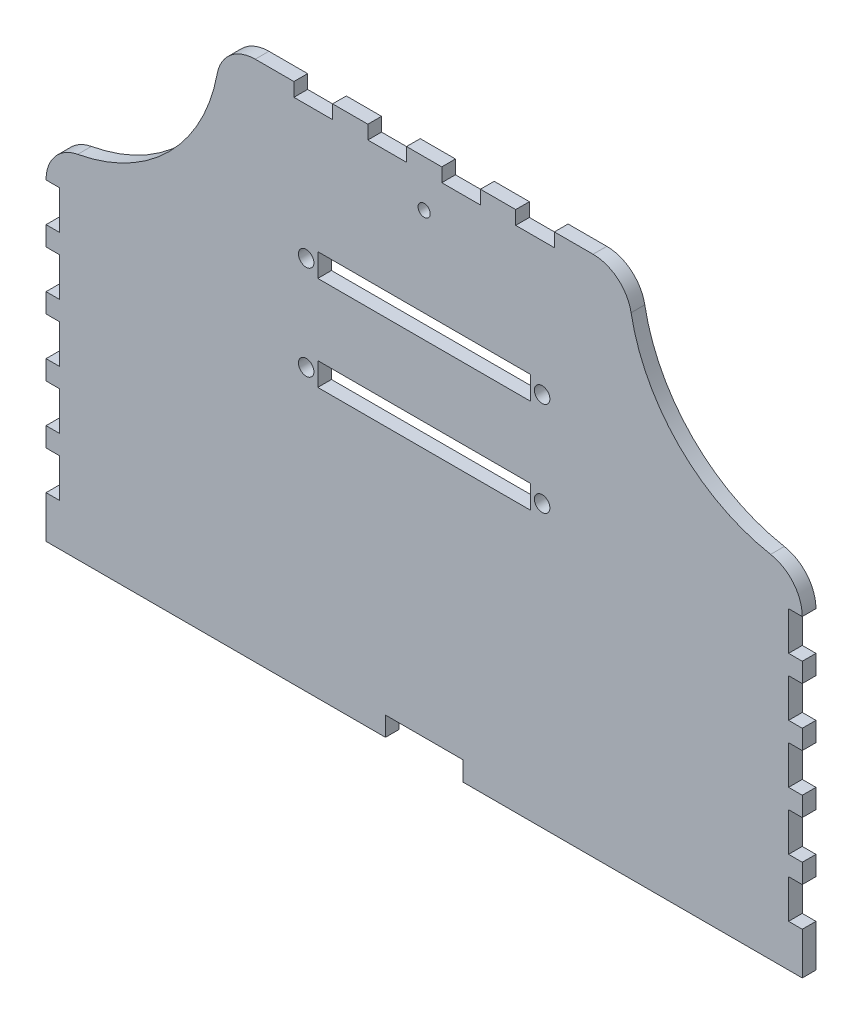
SolidWorks part; units mm, degrees
ref_plane "Front Plane" through (0, 0, 0) normal (0, 0, 1) x (1, 0, 0)
ref_plane "Top Plane" through (0, 0, 0) normal (0, 1, 0) x (1, 0, 0)
ref_plane "Right Plane" through (0, 0, 0) normal (1, 0, 0) x (0, 0, -1)
sketch "Sketch1" plane through (0, 0, 0) normal (0, 0, 1) x (1, 0, 0)
  line L1 (0, 0) -> (248.285, 0)
  line L2 (0, 0) -> (0, 171.45)
  line L3 (0, 171.45) -> (248.285, 171.45)
  line L4 (248.285, 0) -> (248.285, 171.45)
  circle A0 centre (0, 171.45) radius 57.15
  circle A1 centre (248.285, 171.45) radius 57.15
  dimension "D3" = 114.3
  dimension "D1" = 171.45
  dimension "D2" = 248.285
extrude "Boss-Extrude1" add sketch "Sketch1" along normal blind 4.4958 contours A1 L3 A0 L2 L1 L4
fillet "Fillet1" radius 12.7 4 edges at (0, 114.3, 2.2479) (248.285, 114.3, 2.2479) (191.135, 171.45, 2.2479) (57.15, 171.45, 2.2479)
sketch "Sketch2" plane through (0, 0, 4.4958) normal (0, 0, 1) x (1, 0, 0)
  line L0 (0, 83.7142) -> (4.4958, 83.7142)
  line L1 (0, 102.7642) -> (4.4958, 102.7642)
  line L2 (0, 102.7642) -> (0, 90.0642)
  line L3 (0, 90.0642) -> (4.4958, 90.0642)
  line L4 (4.4958, 102.7642) -> (4.4958, 90.0642)
  line L5 (4.4958, 83.7142) -> (4.4958, 71.0142)
  line L6 (0, 71.0142) -> (4.4958, 71.0142)
  line L7 (0, 64.6642) -> (4.4958, 64.6642)
  line L8 (4.4958, 64.6642) -> (4.4958, 51.9642)
  line L9 (0, 51.9642) -> (4.4958, 51.9642)
  line L10 (0, 45.6142) -> (4.4958, 45.6142)
  line L11 (4.4958, 45.6142) -> (4.4958, 32.9142)
  line L12 (0, 32.9142) -> (4.4958, 32.9142)
  line L13 (0, 26.5642) -> (4.4958, 26.5642)
  line L14 (4.4958, 26.5642) -> (4.4958, 13.8642)
  line L15 (0, 13.8642) -> (4.4958, 13.8642)
  line L16 (124.1425, 171.45) -> (124.1425, 0) construction
  line L17 (68.6858, 171.45) -> (179.5992, 171.45) construction
  line L18 (0, 0) -> (248.285, 0) construction
  line L19 (248.285, 13.8642) -> (243.7892, 13.8642)
  line L20 (243.7892, 26.5642) -> (243.7892, 13.8642)
  line L21 (248.285, 26.5642) -> (243.7892, 26.5642)
  line L22 (248.285, 32.9142) -> (243.7892, 32.9142)
  line L23 (243.7892, 45.6142) -> (243.7892, 32.9142)
  line L24 (248.285, 45.6142) -> (243.7892, 45.6142)
  line L25 (248.285, 51.9642) -> (243.7892, 51.9642)
  line L26 (243.7892, 64.6642) -> (243.7892, 51.9642)
  line L27 (248.285, 64.6642) -> (243.7892, 64.6642)
  line L28 (243.7892, 83.7142) -> (243.7892, 71.0142)
  line L29 (248.285, 83.7142) -> (243.7892, 83.7142)
  line L30 (248.285, 71.0142) -> (243.7892, 71.0142)
  line L31 (248.285, 90.0642) -> (243.7892, 90.0642)
  line L32 (243.7892, 102.7642) -> (243.7892, 90.0642)
  line L33 (248.285, 102.7642) -> (243.7892, 102.7642)
  line L34 (248.285, 102.7642) -> (248.285, 90.0642)
  line M20 (0, 102.7642) -> (0, 0)
  line M22 (248.285, 0) -> (248.285, 102.7642)
  dimension "D2" = 4.4958
  dimension "D3" = 12.7
  dimension "D1" = 5
extrude "Cut-Extrude1" cut sketch "Sketch2" against normal through all contours L33 L32 L31 M22 | L30 L29 L28 M22 | L24 L23 L22 M22 | L27 L26 L25 M22 | L21 L20 L19 M22 | L4 L1 L3 M20 | L6 L5 L0 M20 | L9 L8 L7 M20 | L12 L11 L10 M20 | L15 L14 L13 M20
sketch "Sketch3" plane through (0, 0, 4.4958) normal (0, 0, 1) x (1, 0, 0)
  line L0 (105.6569, 171.45) -> (105.6569, 166.9542)
  line L1 (81.3858, 171.45) -> (94.0858, 171.45)
  line L2 (81.3858, 171.45) -> (81.3858, 166.9542)
  line L3 (81.3858, 166.9542) -> (94.0858, 166.9542)
  line L4 (94.0858, 171.45) -> (94.0858, 166.9542)
  line L5 (105.6569, 171.45) -> (118.3569, 171.45)
  line L6 (118.3569, 171.45) -> (118.3569, 166.9542)
  line L7 (105.6569, 166.9542) -> (118.3569, 166.9542)
  line L8 (129.9281, 171.45) -> (129.9281, 166.9542)
  line L9 (129.9281, 171.45) -> (142.6281, 171.45)
  line L10 (142.6281, 171.45) -> (142.6281, 166.9542)
  line L11 (129.9281, 166.9542) -> (142.6281, 166.9542)
  line L12 (154.1992, 171.45) -> (154.1992, 166.9542)
  line L13 (154.1992, 171.45) -> (166.8992, 171.45)
  line L14 (166.8992, 171.45) -> (166.8992, 166.9542)
  line L15 (154.1992, 166.9542) -> (166.8992, 166.9542)
  line L16 (68.6858, 171.45) -> (179.5992, 171.45) construction
  dimension "D1" = 12.7
  dimension "D2" = 12.7
  dimension "D3" = 4.4958
  dimension "D5" = 12.7
  dimension "D4" = 4
extrude "Cut-Extrude2" cut sketch "Sketch3" against normal through all
sketch "Sketch4" [suppressed] plane through (0, 0, 4.4958) normal (0, 0, 1) x (1, 0, 0)
  line L0 (0, 0) -> (248.285, 0) construction
  line L1 (248.285, 0) -> (248.285, 13.8642) construction
  circle A0 centre (210.185, 19.05) radius 5.08
  dimension "D1" = 10.16
  dimension "D2" = 19.05
  dimension "D3" = 38.1
extrude "Cut-Extrude3" [suppressed] cut sketch "Sketch4" against normal through all
sketch "Sketch5" plane through (0, 0, 4.4958) normal (0, 0, 1) x (1, 0, 0)
  line L0 (0, 0) -> (248.285, 0) construction
  line L1 (111.4425, 0) -> (136.8425, 0)
  line L2 (111.4425, 0) -> (111.4425, 6.35)
  line L3 (111.4425, 6.35) -> (136.8425, 6.35)
  line L4 (136.8425, 0) -> (136.8425, 6.35)
  point P6 (124.1425, 0)
  point P7 (124.1425, 0)
  dimension "D1" = 25.4
  dimension "D2" = 6.35
extrude "Cut-Extrude4" cut sketch "Sketch5" against normal through all
sketch "Sketch6" [suppressed] plane through (0, 0, 0) normal (0, 0, -1) x (-1, 0, 0)
  line L0 (-136.8425, 6.35) -> (-111.4425, 6.35) construction
  line L1 (-149.5425, 76.2) -> (-98.7425, 76.2)
  line L2 (-149.5425, 76.2) -> (-149.5425, 50.8)
  line L3 (-149.5425, 50.8) -> (-98.7425, 50.8)
  line L4 (-98.7425, 76.2) -> (-98.7425, 50.8)
  line L5 (0, 0) -> (-111.4425, 0) construction
  point P4 (-124.1425, 50.8)
  point P7 (-124.1425, 6.35)
  dimension "D1" = 50.8
  dimension "D2" = 25.4
  dimension "D3" = 50.8
extrude "Cut-Extrude5" [suppressed] cut sketch "Sketch6" against normal through all
sketch "Sketch7" plane through (0, 0, 0) normal (0, 0, -1) x (-1, 0, 0)
  line L0 (-136.8425, 6.35) -> (-111.4425, 6.35) construction
  line L1 (-159.0675, 127) -> (-89.2175, 127)
  line L2 (-159.0675, 127) -> (-159.0675, 119.38)
  line L3 (-159.0675, 119.38) -> (-89.2175, 119.38)
  line L4 (-89.2175, 127) -> (-89.2175, 119.38)
  line L5 (-159.0675, 96.012) -> (-89.2175, 96.012)
  line L6 (-159.0675, 96.012) -> (-159.0675, 88.392)
  line L7 (-159.0675, 88.392) -> (-89.2175, 88.392)
  line L8 (-89.2175, 96.012) -> (-89.2175, 88.392)
  line L9 (-162.8775, 123.19) -> (-85.4075, 123.19) construction
  line L10 (-118.3569, 171.45) -> (-129.9281, 171.45) construction
  circle A0 centre (-85.4075, 123.19) radius 2.54
  circle A1 centre (-85.4075, 92.202) radius 2.54
  circle A2 centre (-162.8775, 92.202) radius 2.54
  circle A3 centre (-162.8775, 123.19) radius 2.54
  point P10 (-124.1425, 6.35)
  point P11 (-124.1425, 88.392)
  point P20 (-124.1425, 123.19)
  point P23 (-159.0675, 123.19)
  point P24 (-89.2175, 92.202)
  dimension "D3" = 30.988
  dimension "D1" = 5.08
  dimension "D2" = 69.85
  dimension "D4" = 7.62
  dimension "D5" = 77.47
  dimension "D6" = 44.45
extrude "Cut-Extrude6" cut sketch "Sketch7" against normal through all
sketch "Sketch8" plane through (0, 0, 0) normal (0, 0, -1) x (-1, 0, 0)
  line L0 (-118.3569, 171.45) -> (-129.9281, 171.45) construction
  circle A0 centre (-124.1425, 156.21) radius 2
  point P4 (-124.1425, 171.45)
  dimension "D1" = 4
  dimension "D2" = 15.24
extrude "Cut-Extrude7" cut sketch "Sketch8" against normal through all
